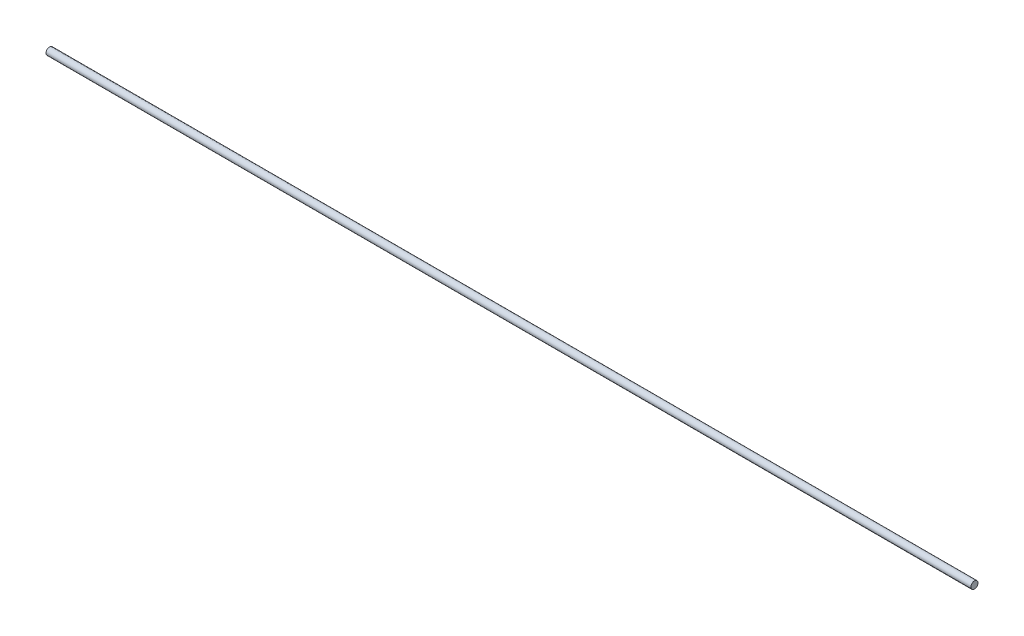
SolidWorks part; units mm, degrees
material "Caoba"
ref_plane "Alzado" through (0, 0, 0) normal (0, 0, 1) x (1, 0, 0)
ref_plane "Planta" through (0, 0, 0) normal (0, 1, 0) x (1, 0, 0)
ref_plane "Vista lateral" through (0, 0, 0) normal (1, 0, 0) x (0, 0, -1)
sketch "Croquis1" plane through (0, 0, 0) normal (1, 0, 0) x (0, 0, -1)
  circle A0 centre (0, 0) radius 2.5
  dimension "D1" = 5
extrude "Saliente-Extruir1" add sketch "Croquis1" along normal blind 645
